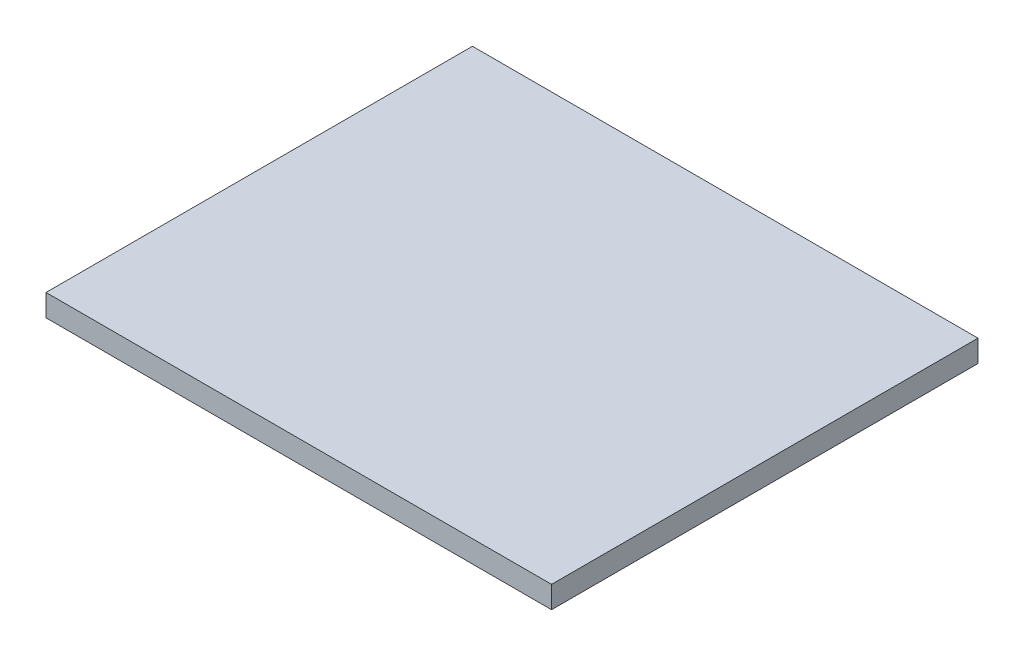
SolidWorks part; units mm, degrees
ref_plane "前视基准面" through (0, 0, 0) normal (0, 0, 1) x (1, 0, 0)
ref_plane "上视基准面" through (0, 0, 0) normal (0, 1, 0) x (1, 0, 0)
ref_plane "右视基准面" through (0, 0, 0) normal (1, 0, 0) x (0, 0, -1)
sketch "草图1" plane through (0, 0, 0) normal (0, 1, 0) x (1, 0, 0)
  line L1 (0, 0) -> (230, 0)
  line L2 (0, 0) -> (0, -194)
  line L3 (0, -194) -> (230, -194)
  line L4 (230, 0) -> (230, -194)
  dimension "D1" = 194
  dimension "D2" = 230
extrude "凸台-拉伸1" add sketch "草图1" along normal blind 10
sketch "草图2" plane through (0, 10, 0) normal (0, 1, 0) x (1, 0, 0)
  line L0 (0, -97) -> (230, -97) construction
  line L1 (0, 0) -> (0, -194) construction
  line L2 (230, -194) -> (230, 0) construction
ref_plane "基准面1" through (0, 0, 97) normal (0, 0, 1) x (1, 0, 0)
